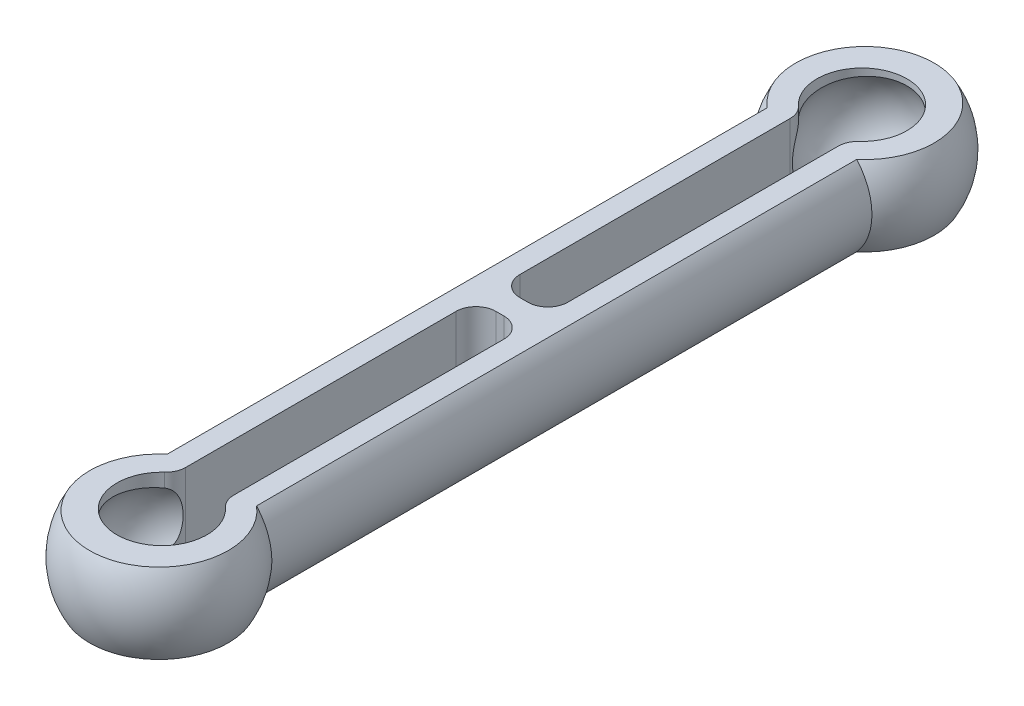
SolidWorks part; units mm, degrees
ref_plane "Front Plane" through (0, 0, 0) normal (0, 0, 1) x (1, 0, 0)
ref_plane "Top Plane" through (0, 0, 0) normal (0, 1, 0) x (1, 0, 0)
ref_plane "Right Plane" through (0, 0, 0) normal (1, 0, 0) x (0, 0, -1)
sketch "Sketch1" plane through (0, 0, 0) normal (0, 1, 0) x (1, 0, 0)
  line L0 (0, 91.3941) -> (0, -96.7552) construction
  line L1 (-73.1408, 0) -> (76.2043, 0) construction
  line L2 (-3, -15) -> (-3, 15)
  line L6 (0, -13.6458) -> (0, 13.6458)
  line L7 (0, 13.6458) -> (0, 14.9458)
  line L8 (0, -13.6458) -> (0, -14.9458)
  line L9 (0, 20.3458) -> (0, 21.6458)
  line L10 (0, -20.3458) -> (0, -21.6458)
  arc A0 (0, 21.6458) -> (-3, 15) centre (0, 17.6458) ccw
  arc A2 (0, -21.6458) -> (-3, -15) centre (0, -17.6458) cw
  arc A3 (0, 20.3458) -> (0, 14.9458) centre (0, 17.6458) ccw
  arc A4 (0, -14.9458) -> (0, -20.3458) centre (0, -17.6458) ccw
  dimension "D5" = 4
  dimension "D6" = 5.4
  dimension "D7" = 5.4
  dimension "D1" = 3
  dimension "D2" = 8
  dimension "D3" = 30
  dimension "D4" = 3
revolve "Revolve1" add sketch "Sketch1" angle 360 about L0
sketch "Sketch2" plane through (0, 0, 0) normal (0, 1, 0) x (1, 0, 0)
  line L0 (0, 0) -> (0, 74.3344) construction
  line L1 (0, 0) -> (0, -69.9604) construction
  line L2 (-1.2, 15.1078) -> (-1.2, 1.5967)
  line L3 (-0.2, 0.5967) -> (0.2, 0.5967)
  line L4 (1.2, 1.5967) -> (1.2, 15.1078)
  line L5 (0, 0) -> (14.3556, 0) construction
  line L6 (-1.2, -15.1078) -> (-1.2, -1.5967)
  line L7 (-0.2, -0.5967) -> (0.2, -0.5967)
  line L8 (1.2, -1.5967) -> (1.2, -15.1078)
  arc A0 (1.5231, 15.8439) -> (-1.5231, 15.8439) centre (0, 17.5) ccw
  arc A2 (1.5231, -15.8439) -> (-1.5231, -15.8439) centre (0, -17.5) cw
  arc A3 (-1.2, 15.1078) -> (-1.5231, 15.8439) centre (-2.2, 15.1078) ccw
  arc A4 (1.2, 15.1078) -> (1.5231, 15.8439) centre (2.2, 15.1078) cw
  arc A5 (-1.2, 1.5967) -> (-0.2, 0.5967) centre (-0.2, 1.5967) ccw
  arc A6 (0.2, 0.5967) -> (1.2, 1.5967) centre (0.2, 1.5967) ccw
  arc A7 (-1.5231, -15.8439) -> (-1.2, -15.1078) centre (-2.2, -15.1078) ccw
  arc A8 (1.5231, -15.8439) -> (1.2, -15.1078) centre (2.2, -15.1078) cw
  arc A9 (0.2, -0.5967) -> (1.2, -1.5967) centre (0.2, -1.5967) cw
  arc A10 (-1.2, -1.5967) -> (-0.2, -0.5967) centre (-0.2, -1.5967) cw
  point P17 (-1.2, 15.5967)
  point P20 (1.2, 15.5967)
  point P23 (-1.2, 0.5967)
  point P26 (1.2, 0.5967)
  point P29 (-1.2, -15.5967)
  point P32 (1.2, -15.5967)
  point P35 (1.2, -0.5967)
  point P38 (-1.2, -0.5967)
  dimension "D1" = 4.5
  dimension "D3" = 1
  dimension "D2" = 17.5
  dimension "D5" = 1.2
  dimension "D6" = 1.2
  dimension "D7" = 15
extrude "Cut-Extrude1" cut sketch "Sketch2" against normal mid plane 60
sketch "Sketch3" plane through (0, 0, 0) normal (1, 0, 0) x (0, 0, -1)
  line L0 (0, -2) -> (70.025, -2)
  line L1 (70.025, -2) -> (70.025, -4)
  line L2 (70.025, -4) -> (-79.975, -4)
  line L3 (-79.975, -4) -> (-79.975, -2)
  line L4 (-79.975, -2) -> (0, -2)
  line L5 (73.071, 0) -> (-75.6054, 0) construction
  line L6 (0, 2) -> (70.025, 2)
  line L7 (-79.975, 2) -> (0, 2)
  line L8 (-79.975, 4) -> (-79.975, 2)
  line L9 (70.025, 4) -> (-79.975, 4)
  line L10 (70.025, 4) -> (70.025, 2)
  dimension "D1" = 2
  dimension "D2" = 2
  dimension "D3" = 150
  dimension "D4" = 80
extrude "Cut-Extrude2" cut sketch "Sketch3" against normal mid plane 60
